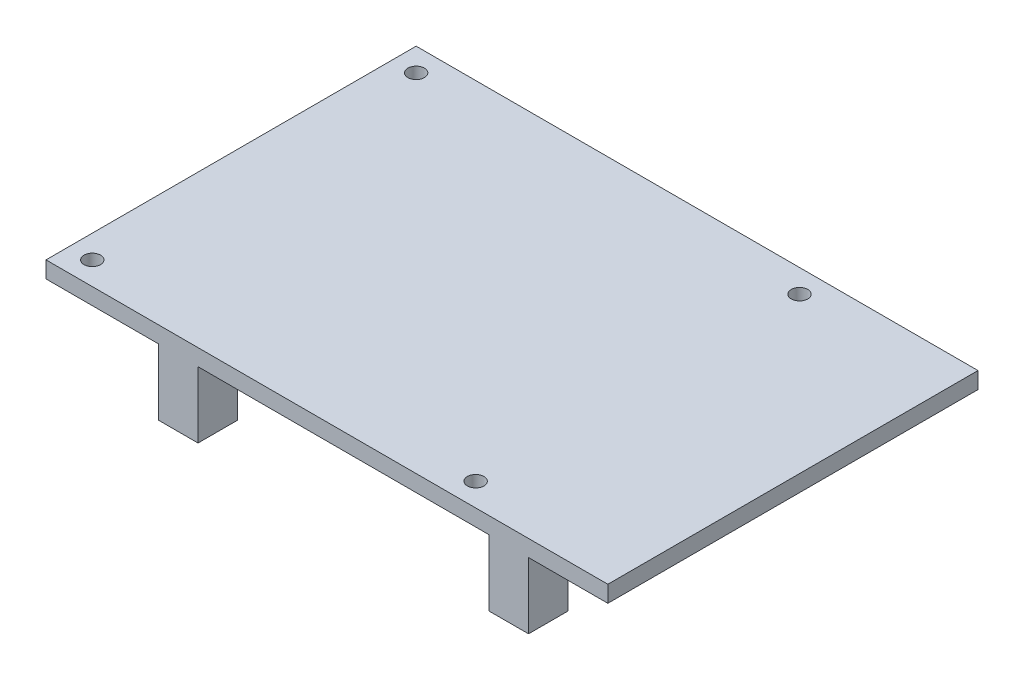
SolidWorks part; units mm, degrees
ref_plane "Front Plane" through (0, 0, 0) normal (0, 0, 1) x (1, 0, 0)
ref_plane "Top Plane" through (0, 0, 0) normal (0, 1, 0) x (1, 0, 0)
ref_plane "Right Plane" through (0, 0, 0) normal (1, 0, 0) x (0, 0, -1)
sketch "Sketch1" plane through (0, 0, 0) normal (0, 1, 0) x (1, 0, 0)
  line L1 (0, 0) -> (85, 0)
  line L2 (0, 0) -> (0, -56)
  line L3 (0, -56) -> (85, -56)
  line L4 (85, 0) -> (85, -56)
  dimension "D1" = 85
  dimension "D2" = 56
extrude "Boss-Extrude1" add sketch "Sketch1" along normal blind 2.5
sketch "Sketch2" plane through (0, 2.5, 0) normal (0, 1, 0) x (1, 0, 0)
  line L0 (0, -3.5) -> (85, -3.5) construction
  line L1 (0, 0) -> (0, -56) construction
  line L2 (85, -56) -> (85, 0) construction
  line L3 (0, -52.5) -> (85, -52.5) construction
  line L4 (3.5, 0) -> (3.5, -56) construction
  line L5 (85, 0) -> (0, 0) construction
  line L6 (0, -56) -> (85, -56) construction
  line L7 (61.5, 0) -> (61.5, -56) construction
  point P17 (61.5, -3.5)
  point P21 (61.5, -52.5)
  point P22 (3.5, -52.5)
  point P24 (3.5, -3.5)
  dimension "D1" = 58
  dimension "D2" = 3.5
  dimension "D3" = 3.5
  dimension "D4" = 3.5
hole_wizard "Tap Drill for M3x0.5 Tap2" positions "Sketch2" profile "Sketch4" hole size "M3x0.5" standard "ANSI Metric" end condition through all
sketch "Sketch4" plane through (3.5, 2.5, 3.5) normal (1, 0, 0) x (0, 0, 1)
  line L0 (0, 0) -> (0, 2.5)
  line L1 (0, 2.5) -> (1.25, 2.5)
  line L2 (1.25, 2.5) -> (1.25, 0)
  line L5 (1.25, 0) -> (0, 0)
  line L11 (0, -6.35) -> (0, 107.95) construction
  dimension "Thru Hole Dia." = 2.5
  dimension "Thru Hole Depth" = 2.5
sketch "Sketch5" plane through (0, 0, 0) normal (0, -1, 0) x (1, 0, 0)
  line L0 (85, 0) -> (0, 0) construction
  line L1 (17, 6) -> (23, 6)
  line L2 (17, 6) -> (17, 0)
  line L3 (17, 0) -> (23, 0)
  line L4 (23, 6) -> (23, 0)
  line L5 (17, 56) -> (23, 56)
  line L6 (17, 56) -> (17, 50)
  line L7 (17, 50) -> (23, 50)
  line L8 (23, 56) -> (23, 50)
  line L9 (67, 56) -> (73, 56)
  line L10 (67, 56) -> (67, 50)
  line L11 (67, 50) -> (73, 50)
  line L12 (73, 56) -> (73, 50)
  line L13 (67, 6) -> (73, 6)
  line L14 (67, 6) -> (67, 0)
  line L15 (67, 0) -> (73, 0)
  line L16 (73, 6) -> (73, 0)
  line L17 (20, 56) -> (20, 0) construction
  line L18 (0, 56) -> (85, 56) construction
  line L19 (17, 6) -> (23, 0) construction
  line L20 (17, 50) -> (23, 56) construction
  line L21 (67, 56) -> (73, 50) construction
  line L22 (73, 6) -> (67, 0) construction
  line L23 (70, 53) -> (70, 3) construction
  line L24 (85, 56) -> (85, 0) construction
  point P24 (20, 3)
  point P25 (20, 53)
  line M26 (0, 0) -> (85, 0)
  line M28 (85, 56) -> (0, 56)
  dimension "D1" = 6
  dimension "D2" = 20
  dimension "D3" = 15
extrude "Boss-Extrude2" add sketch "Sketch5" along normal blind 10 contours L4 L1 L2 M26 | L8 L6 L7 M28 | L14 L13 L16 L15 | L10 L9 L12 L11
